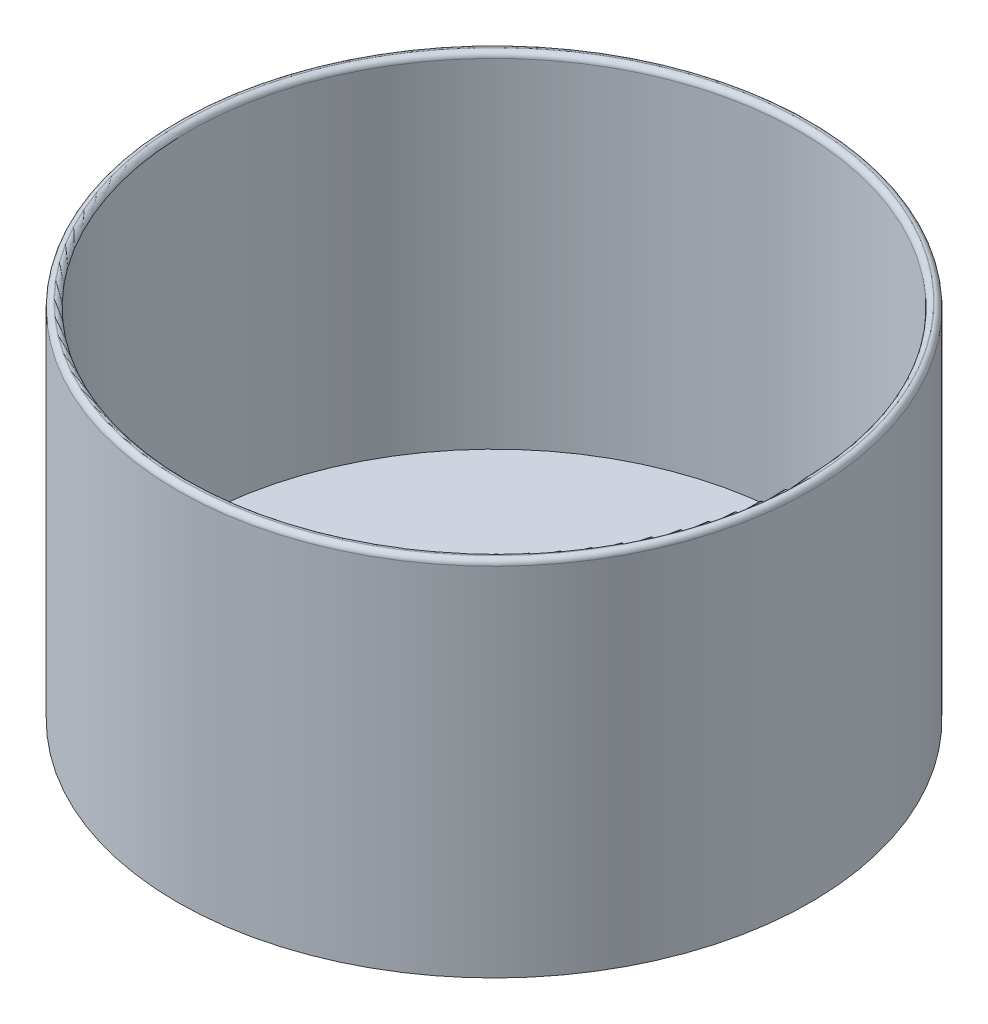
SolidWorks part; units mm, degrees
ref_plane "Front Plane" through (0, 0, 0) normal (0, 0, 1) x (1, 0, 0)
ref_plane "Top Plane" through (0, 0, 0) normal (0, 1, 0) x (1, 0, 0)
ref_plane "Right Plane" through (0, 0, 0) normal (1, 0, 0) x (0, 0, -1)
sketch "Sketch1" plane through (0, 0, 0) normal (0, 1, 0) x (1, 0, 0)
  line L1 (0, 0) -> (12.7, 0)
  line L2 (0, 0) -> (0, 12.7)
  line L3 (0, 12.7) -> (12.7, 12.7)
  line L4 (12.7, 0) -> (12.7, 12.7)
  dimension "D1" = 12.7
  dimension "D2" = 12.7
extrude "Boss-Extrude1" add sketch "Sketch1" along normal blind 12.7
sketch "Sketch2" plane through (0, 12.7, 0) normal (0, 1, 0) x (1, 0, 0)
  circle A0 centre (6.35, 6.35) radius 88.9
  dimension "D1" = 177.8
extrude "Boss-Extrude2" add sketch "Sketch2" along normal blind 101.6
sketch "Sketch3" plane through (0, 114.3, 0) normal (0, 1, 0) x (1, 0, 0)
  circle A0 centre (6.35, 6.35) radius 85.725
  dimension "D1" = 171.45
extrude "Cut-Extrude1" cut sketch "Sketch3" against normal blind 96.52
sketch "Sketch4" plane through (0, 0, 0) normal (0, -1, 0) x (1, 0, 0)
  line L1 (0, 0) -> (12.7, 0)
  line L2 (0, 0) -> (0, -12.7)
  line L3 (0, -12.7) -> (12.7, -12.7)
  line L4 (12.7, 0) -> (12.7, -12.7)
extrude "Cut-Extrude2" cut sketch "Sketch4" against normal blind 12.7
fillet "Fillet2" radius 1.524 2 edges at (6.35, 114.3, 82.55) (6.35, 114.3, 79.375)
